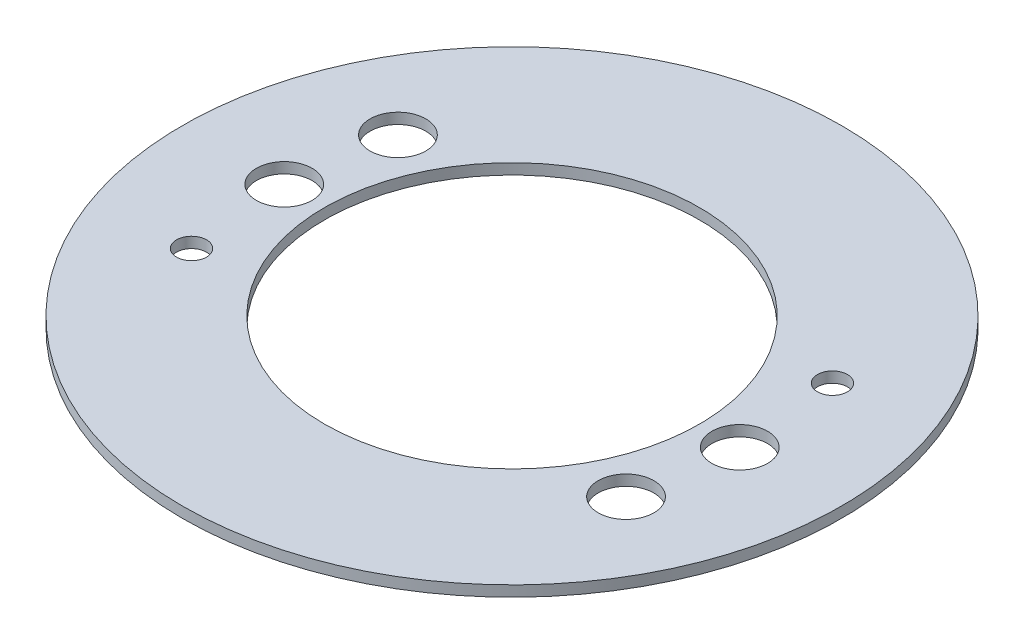
SolidWorks part; units mm, degrees
ref_plane "Front Plane" through (0, 0, 0) normal (0, 0, 1) x (1, 0, 0)
ref_plane "Top Plane" through (0, 0, 0) normal (0, 1, 0) x (1, 0, 0)
ref_plane "Right Plane" through (0, 0, 0) normal (1, 0, 0) x (0, 0, -1)
sketch "Sketch1" plane through (0, 0, 0) normal (0, 1, 0) x (1, 0, 0)
  circle A0 centre (0, 0) radius 78.105
  circle A1 centre (0, 0) radius 44.45
extrude "Boss-Extrude1" add sketch "Sketch1" along normal blind 2.54
sketch "Sketch2" plane through (0, 2.54, 0) normal (0, 1, 0) x (1, 0, 0)
  line L0 (53.975, 0) -> (-53.975, 0) construction
  line L1 (51.7955, 24.1526) -> (-51.7955, -24.1526) construction
  line L2 (0, 0) -> (50.6445, -23.6159) construction
  line L3 (0, 0) -> (-50.6445, 23.6159) construction
  circle A0 centre (-53.975, 0) radius 6.604
  circle A1 centre (53.975, 0) radius 6.604
  circle A2 centre (-51.7955, -24.1526) radius 3.556
  circle A3 centre (51.7955, 24.1526) radius 3.556
  circle A4 centre (50.6445, -23.6159) radius 6.604
  circle A5 centre (-50.6445, 23.6159) radius 6.604
  point P4 (0, 0)
  point P10 (0, 0)
extrude "Cut-Extrude1" cut sketch "Sketch2" against normal blind 2.54
